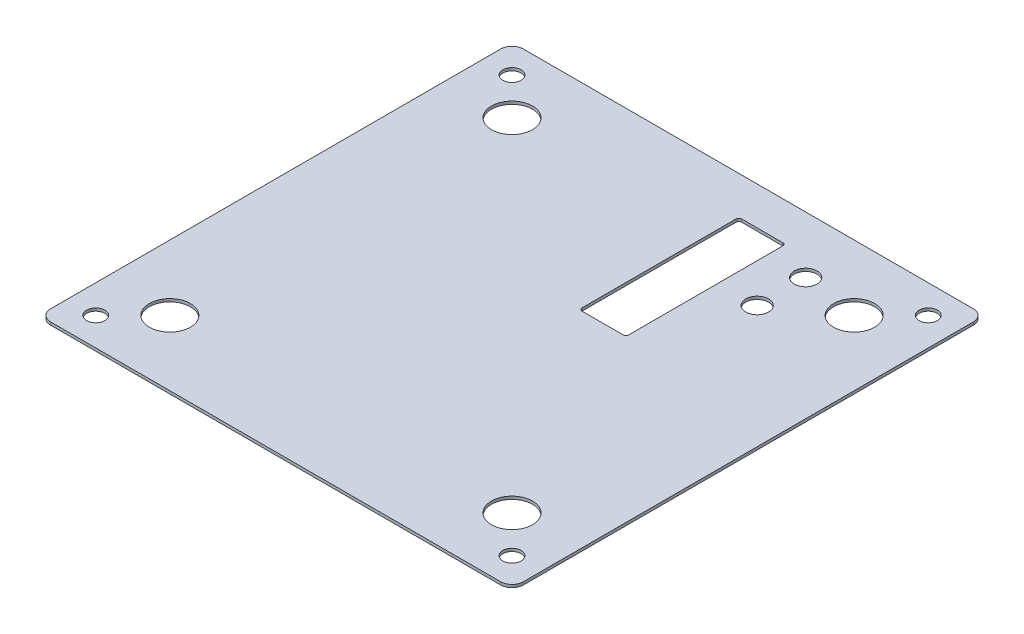
SolidWorks part; units mm, degrees
material "Thornel Mat VMA"
ref_plane "Front Plane" through (0, 0, 0) normal (0, 0, 1) x (1, 0, 0)
ref_plane "Top Plane" through (0, 0, 0) normal (0, 1, 0) x (1, 0, 0)
ref_plane "Right Plane" through (0, 0, 0) normal (1, 0, 0) x (0, 0, -1)
sketch "Sketch1" plane through (0, 0, 0) normal (0, 1, 0) x (1, 0, 0)
  line L1 (-41.45, -41.45) -> (41.45, -41.45)
  line L2 (-41.45, -41.45) -> (-41.45, 41.45)
  line L3 (-41.45, 41.45) -> (41.45, 41.45)
  line L4 (41.45, -41.45) -> (41.45, 41.45)
  line L5 (-41.45, -41.45) -> (41.45, 41.45) construction
  line L6 (-41.45, 41.45) -> (41.45, -41.45) construction
  point P0 (0, 0)
  dimension "D1" = 82.9
  dimension "D2" = 82.9
extrude "Boss-Extrude1" add sketch "Sketch1" along normal blind 0.5
sketch "Sketch2" plane through (0, 0.5, 0) normal (0, 1, 0) x (1, 0, 0)
  line L0 (0, 41.45) -> (0, -41.45) construction
  line L1 (41.45, 41.45) -> (-41.45, 41.45) construction
  line L2 (-41.45, -41.45) -> (41.45, -41.45) construction
  line L4 (-30, -30) -> (30, -30) construction
  line L5 (-30, -30) -> (-30, 30) construction
  line L6 (-30, 30) -> (30, 30) construction
  line L7 (30, -30) -> (30, 30) construction
  line L8 (-30, -30) -> (30, 30) construction
  line L9 (-30, 30) -> (30, -30) construction
  circle A0 centre (-30, 30) radius 3.6
  circle A1 centre (30, 30) radius 3.6
  circle A2 centre (30, -30) radius 3.6
  circle A3 centre (-30, -30) radius 3.6
  point P6 (0, 0)
  dimension "D2" = 7.2
  dimension "D1" = 60
extrude "Cut-Extrude1" cut sketch "Sketch2" against normal through all
fillet "Fillet1" radius 2 4 edges at (-41.45, 0.25, -41.45) (41.45, 0.25, -41.45) (41.45, 0.25, 41.45) (-41.45, 0.25, 41.45)
sketch "Sketch3" plane through (0, 0.5, 0) normal (0, 1, 0) x (1, 0, 0)
  line L1 (-36.5, -36.5) -> (36.5, -36.5) construction
  line L2 (-36.5, -36.5) -> (-36.5, 36.5) construction
  line L3 (-36.5, 36.5) -> (36.5, 36.5) construction
  line L4 (36.5, -36.5) -> (36.5, 36.5) construction
  line L5 (-36.5, -36.5) -> (36.5, 36.5) construction
  line L6 (-36.5, 36.5) -> (36.5, -36.5) construction
  circle A0 centre (-36.5, 36.5) radius 1.6
  circle A1 centre (36.5, 36.5) radius 1.6
  circle A2 centre (36.5, -36.5) radius 1.6
  circle A3 centre (-36.5, -36.5) radius 1.6
  point P0 (0, 0)
  dimension "D1" = 3.2
  dimension "D5" = 73
  dimension "D6" = 73
extrude "Cut-Extrude2" cut sketch "Sketch3" against normal blind 10
sketch "Sketch4" plane through (0, 0.5, 0) normal (0, 1, 0) x (1, 0, 0)
  circle A0 centre (20, 31.4998) radius 2
  circle A1 centre (20, 22.9998) radius 2
  dimension "D1" = 4
extrude "Cut-Extrude3" cut sketch "Sketch4" against normal blind 10
sketch "Sketch6" plane through (0, 0.5, 0) normal (0, 1, 0) x (1, 0, 0)
  line L0 (-18.6, 35.12) -> (-18.6, 27.5) construction
  line L1 (-16.78, 27.62) -> (11.22, 27.62)
  line L2 (-16.78, 27.62) -> (-16.78, 35.82)
  line L3 (-16.78, 35.82) -> (11.22, 35.82)
  line L4 (11.22, 27.62) -> (11.22, 35.82)
  line L5 (-16.78, 27.62) -> (11.22, 35.82) construction
  line L6 (-16.78, 35.82) -> (11.22, 27.62) construction
  line L7 (-18.6, 31.31) -> (-2.78, 31.72) construction
  circle A2 centre (-18.6, 27.5) radius 0.4572 construction
  point P0 (-2.78, 31.72)
  dimension "D1" = 0.41
  dimension "D2" = 28
  dimension "D3" = 8.2
  dimension "D4" = 1.82
extrude "Cut-Extrude4" [suppressed] cut sketch "Sketch6" against normal blind 10
fillet "Fillet2" [suppressed] radius 0.5
sketch "Sketch7" plane through (0, 0.5, 0) normal (0, 1, 0) x (1, 0, 0)
  line L0 (5.3372, 36.6) -> (12.0428, 36.6) construction
  line L1 (8.69, 36.6) -> (9.1, 20.78) construction
  line L2 (5, 6.78) -> (13.2, 6.78)
  line L3 (5, 6.78) -> (5, 34.78)
  line L4 (5, 34.78) -> (13.2, 34.78)
  line L5 (13.2, 6.78) -> (13.2, 34.78)
  line L6 (5, 6.78) -> (13.2, 34.78) construction
  line L7 (5, 34.78) -> (13.2, 6.78) construction
  circle A0 centre (4.88, 36.6) radius 0.4572 construction
  circle A1 centre (12.5, 36.6) radius 0.4572 construction
  point P7 (9.1, 20.78)
  dimension "D1" = 0.41
  dimension "D2" = 8.2
  dimension "D3" = 28
  dimension "D4" = 1.82
extrude "Cut-Extrude5" cut sketch "Sketch7" against normal blind 10
fillet "Fillet3" radius 0.5 4 edges at (5, 0.25, -6.78) (13.2, 0.25, -6.78) (13.2, 0.25, -34.78) (5, 0.25, -34.78)
